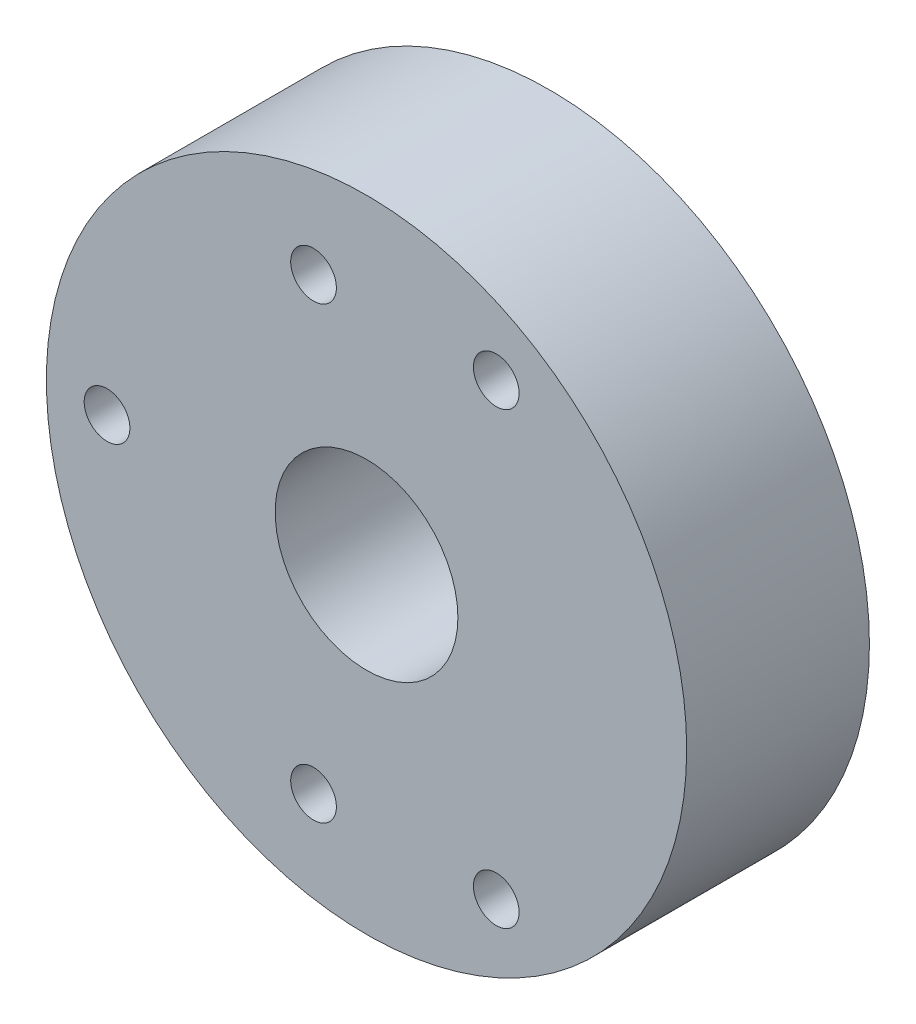
SolidWorks part; units mm, degrees
ref_plane "Front Plane" through (0, 0, 0) normal (0, 0, 1) x (1, 0, 0)
ref_plane "Top Plane" through (0, 0, 0) normal (0, 1, 0) x (1, 0, 0)
ref_plane "Right Plane" through (0, 0, 0) normal (1, 0, 0) x (0, 0, -1)
sketch "Sketch1" plane through (0, 0, 0) normal (0, 0, 1) x (1, 0, 0)
  circle A0 centre (0, 0) radius 44.5003
  circle A1 centre (0, 0) radius 12.7
  circle A4 centre (-36.068, 0) radius 3.175
  circle A7 centre (18.034, 31.2358) radius 3.175
  circle A8 centre (18.034, -31.2358) radius 3.175
  dimension "D1" = 89.0005
  dimension "D2" = 25.4
  dimension "D6" = 6.35
  dimension "D7" = 6.35
  dimension "D8" = 6.35
extrude "Boss-Extrude1" add sketch "Sketch1" along normal blind 25.4
sketch "Sketch2" plane through (0, 0, 25.4) normal (0, 0, 1) x (1, 0, 0)
  line L0 (18.034, -31.2358) -> (-7.366, -31.2358) construction
  line L1 (-7.366, -31.2358) -> (-7.366, 31.2358) construction
  line L2 (-7.366, 31.2358) -> (18.034, 31.2358) construction
  line L3 (18.034, 31.2358) -> (18.034, -31.2358) construction
  circle A0 centre (-7.366, -31.2358) radius 3.175
  circle A1 centre (-7.366, 31.2358) radius 3.175
  dimension "D3" = 6.35
  dimension "D4" = 6.35
  dimension "D1" = 25.4
  dimension "D2" = 90
extrude "Cut-Extrude1" cut sketch "Sketch2" against normal blind 25.4
